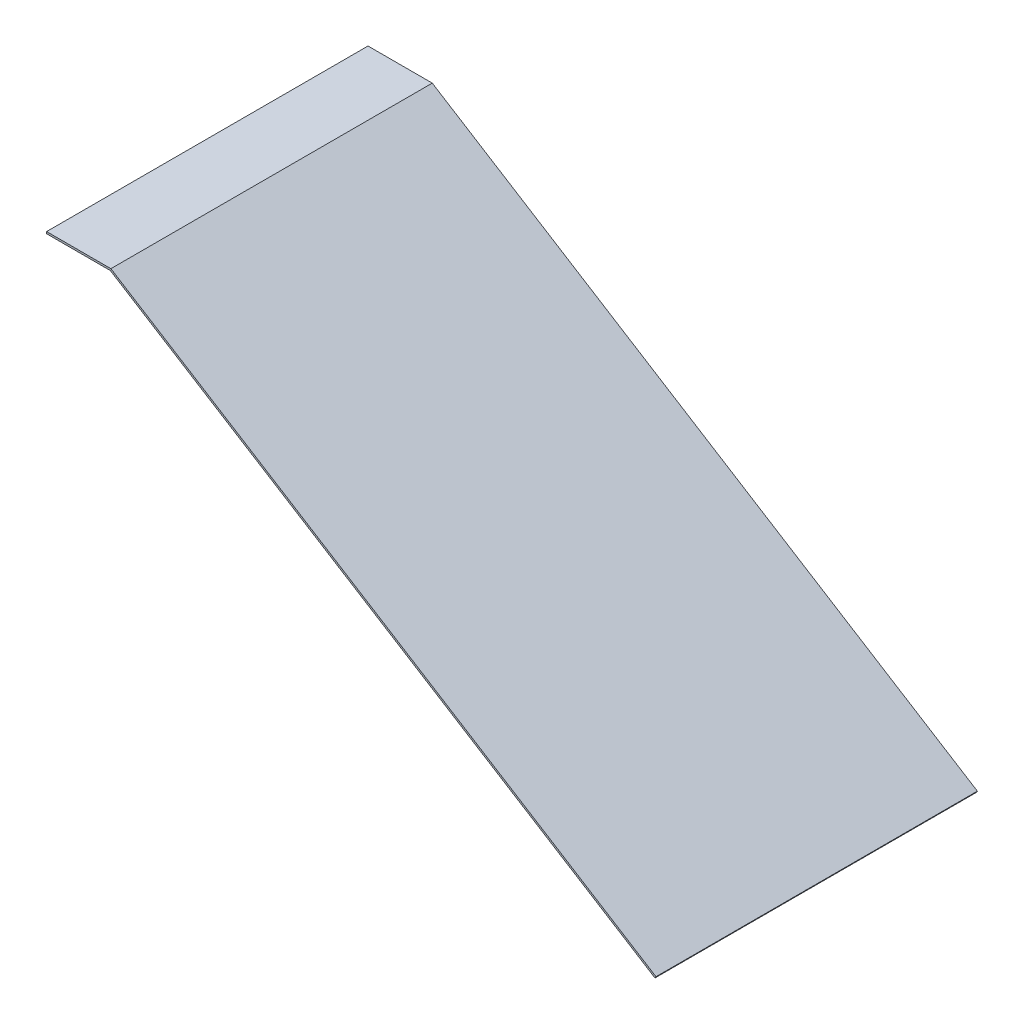
SolidWorks part; units mm, degrees
ref_plane "前视基准面" through (0, 0, 0) normal (0, 0, 1) x (1, 0, 0)
ref_plane "上视基准面" through (0, 0, 0) normal (0, 1, 0) x (1, 0, 0)
ref_plane "右视基准面" through (0, 0, 0) normal (1, 0, 0) x (0, 0, -1)
other "Configuration Table"
sketch "草图1" plane through (0, 0, 0) normal (0, 0, 1) x (1, 0, 0)
  line L0 (50, 562.7521) -> (150, 562.7521)
  line L1 (150, 562.7521) -> (998.0481, 32.8329)
  line L2 (998.0481, 32.8329) -> (996.4583, 30.2887)
  line L3 (996.4583, 30.2887) -> (150, 559.2146)
  line L4 (150, 559.2146) -> (150, 559.7521)
  line L5 (150, 559.7521) -> (50, 559.7521)
  line L6 (50, 559.7521) -> (50, 562.7521)
extrude "304_deck_normal_t3_and_horizontal_platform_t3" add sketch "草图1" along normal blind 500 separate body
